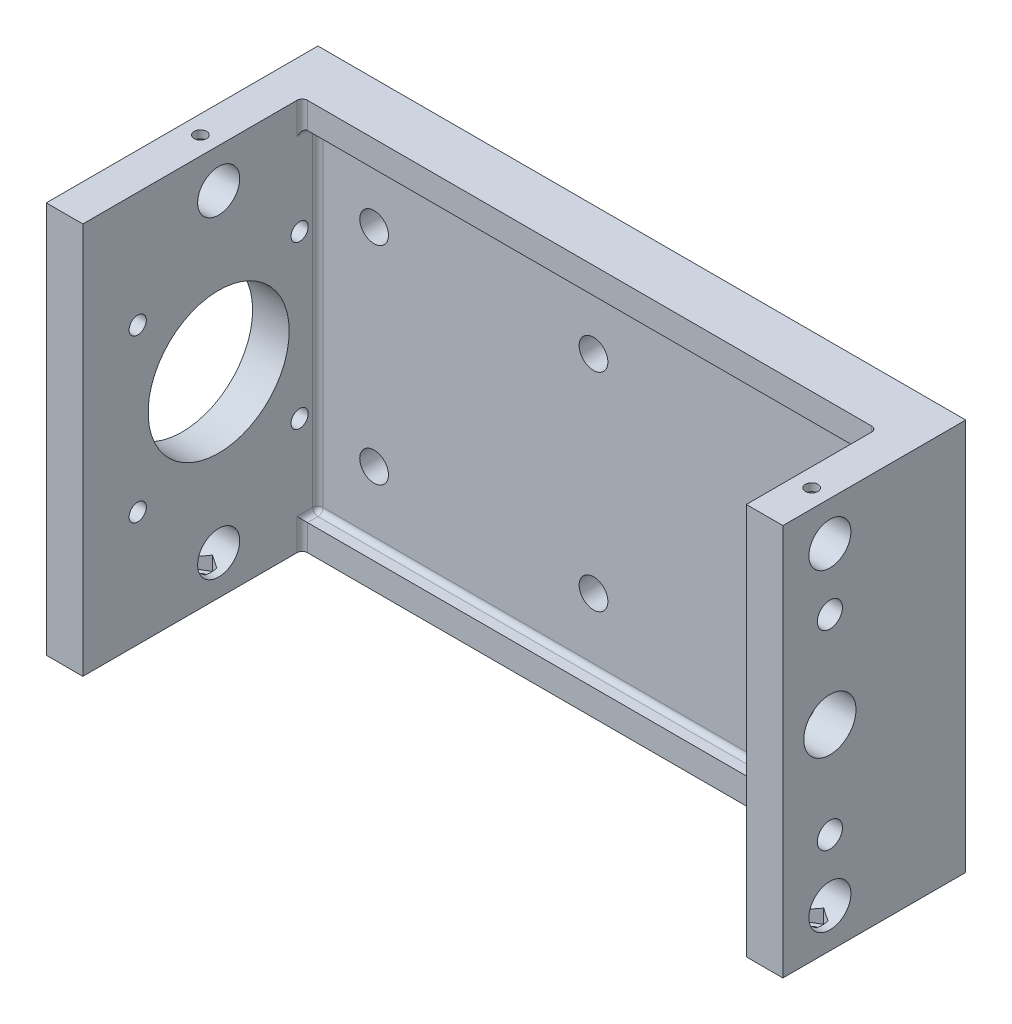
SolidWorks part; units mm, degrees
ref_plane "Plan de face" through (0, 0, 0) normal (0, 0, 1) x (1, 0, 0)
ref_plane "Plan de dessus" through (0, 0, 0) normal (0, 1, 0) x (1, 0, 0)
ref_plane "Plan de droite" through (0, 0, 0) normal (1, 0, 0) x (0, 0, -1)
sketch "Sketch1" plane through (0, 0, 0) normal (0, 0, 1) x (1, 0, 0)
  line L1 (55, -37.5) -> (-55, -37.5)
  line L2 (55, -37.5) -> (55, 37.5)
  line L3 (55, 37.5) -> (-55, 37.5)
  line L4 (-55, -37.5) -> (-55, 37.5)
  line L5 (55, -37.5) -> (-55, 37.5) construction
  line L6 (55, 37.5) -> (-55, -37.5) construction
  point P0 (0, 0)
  dimension "D1" = 110
  dimension "D2" = 75
extrude "Boss-Extrude1" add sketch "Sketch1" along normal blind 5
sketch "Sketch2" plane through (-55, 0, 0) normal (-1, 0, 0) x (0, 0, 1)
  line L0 (5, -37.5) -> (0, -37.5) construction
  line L1 (0, 37.5) -> (50, 37.5)
  line L2 (0, 37.5) -> (0, -37.5)
  line L3 (0, -37.5) -> (50, -37.5)
  line L4 (50, 37.5) -> (50, -37.5)
  line L6 (45, -16.5858) -> (45, 16.5858) construction
  dimension "D1" = 5
extrude "Boss-Extrude2" add sketch "Sketch2" along normal blind 7
sketch "Sketch3" plane through (55, 0, 0) normal (1, 0, 0) x (0, 0, -1)
  line L10 (0, 37.5) -> (-50, 37.5)
  line L11 (0, 37.5) -> (0, -37.5)
  line L12 (0, -37.5) -> (-50, -37.5)
  line L13 (-50, 37.5) -> (-50, -37.5)
extrude "Boss-Extrude3" add sketch "Sketch3" along normal blind 7
sketch "Sketch4" plane through (-55, 0, 0) normal (1, 0, 0) x (0, 0, -1)
  circle A0 centre (-24, 0) radius 13.5
  dimension "D1" = 27
extrude "Cut-Extrude1" cut sketch "Sketch4" against normal through all
sketch "Sketch5" plane through (-62, 0, 0) normal (-1, 0, 0) x (0, 0, 1)
  circle A0 centre (39.5, 15.5) radius 1.65
  circle A1 centre (39.5, -15.5) radius 1.65
  circle A2 centre (8.5, -15.5) radius 1.65
  circle A3 centre (8.5, 15.5) radius 1.65
  dimension "D1" = 3.3
  dimension "D2" = 3.3
  dimension "D3" = 3.3
  dimension "D4" = 3.3
extrude "Cut-Extrude2" cut sketch "Sketch5" against normal up to surface (7 mm away) up to face at (-55, 0, 10.5)
sketch "Sketch8" plane through (-62, 0, 0) normal (-1, 0, 0) x (0, 0, 1)
  circle A0 centre (24, 30) radius 4.025
  dimension "D1" = 8.05
extrude "Cut-Extrude5" cut sketch "Sketch8" against normal through all
mirror "Mirror1" about plane through (0, 0, 0) normal (0, 1, 0) of "Cut-Extrude5"
sketch "Sketch9" plane through (55, 0, 0) normal (-1, 0, 0) x (0, 0, 1)
  line L0 (50, -37.5) -> (5, -37.5) construction
  line L1 (50, 37.5) -> (33, 37.5)
  line L2 (50, 37.5) -> (50, -37.5)
  line L3 (50, -37.5) -> (33, -37.5)
  line L4 (33, 37.5) -> (33, -37.5)
  dimension "D1" = 17
extrude "Cut-Extrude6" cut sketch "Sketch9" against normal through all
sketch "Sketch13" plane through (0, 0, 0) normal (0, 0, -1) x (-1, 0, 0)
  line L1 (62, 37.5) -> (62, -37.5) construction
  circle A0 centre (44.25, 19.85) radius 2.75
  circle A1 centre (2.25, 19.85) radius 2.75
  circle A2 centre (2.25, -19.85) radius 2.75
  circle A3 centre (44.25, -19.85) radius 2.75
  dimension "D1" = 5.5
  dimension "D2" = 5.5
  dimension "D3" = 5.5
  dimension "D4" = 5.5
  dimension "D5" = 17.75
  dimension "D6" = 42
extrude "Cut-Extrude7" cut sketch "Sketch13" against normal blind 10
sketch "Sketch14" plane through (55, 0, 0) normal (-1, 0, 0) x (0, 0, 1)
  circle A0 centre (24, 0) radius 5
  dimension "D1" = 10
extrude "Cut-Extrude8" cut sketch "Sketch14" against normal blind 10
sketch "Sketch15" plane through (0, 0, 0) normal (0, 0, -1) x (-1, 0, 0)
  line L4 (-62, -37.5) -> (62, -37.5)
  line L5 (62, -37.5) -> (62, 37.5)
  line L6 (62, 37.5) -> (-62, 37.5)
  line L7 (-62, 37.5) -> (-62, -37.5)
  line L8 (-62, -37.5) -> (62, -37.5)
  line L9 (62, -37.5) -> (62, 37.5)
  line L10 (62, 37.5) -> (-62, 37.5)
  line L11 (-62, 37.5) -> (-62, -37.5)
  circle A1 centre (44.25, 19.85) radius 2.75
  circle A2 centre (44.25, 19.85) radius 2.75
  circle A4 centre (2.25, 19.85) radius 2.75
  circle A5 centre (2.25, -19.85) radius 2.75
  circle A6 centre (2.25, -19.85) radius 2.75
  circle A7 centre (44.25, -19.85) radius 2.75
  circle A8 centre (44.25, -19.85) radius 2.75
  point P6 (0, 19.85)
  dimension "D1" = 0
  dimension "D3" = 0
  dimension "D4" = 0
  dimension "D5" = 0
extrude "Boss-Extrude4" add sketch "Sketch15" along normal blind 2
ref_plane "Plane1" through (0, -34.025, 0) normal (0, 1, 0) x (1, 0, 0)
sketch "Sketch16" plane through (0, -34.025, 0) normal (0, 1, 0) x (1, 0, 0)
  line L0 (62, -33) -> (55, -33) construction
  line L1 (58.5, -26.3094) -> (60.5, -25.1547)
  line L2 (60.5, -25.1547) -> (60.5, -22.8453)
  line L3 (60.5, -22.8453) -> (58.5, -21.6906)
  line L4 (58.5, -21.6906) -> (56.5, -22.8453)
  line L5 (56.5, -22.8453) -> (56.5, -25.1547)
  line L6 (56.5, -25.1547) -> (58.5, -26.3094)
  line L7 (55, -5) -> (55, -33) construction
  circle A0 centre (58.5, -24) radius 2 construction
  dimension "D2" = 4
  dimension "D1" = 9
  dimension "D3" = 3.5
extrude "Cut-Extrude11" cut sketch "Sketch16" against normal blind 2 and the other way blind 2
hole_wizard "Dégagement M21" positions "Sketch17" profile "Sketch18" hole size "M2" standard "ISO"
sketch "Sketch17" plane through (0, -37.5, 0) normal (0, -1, 0) x (-1, 0, 0)
  line L0 (-62, -33) -> (-55, -33) construction
  line L1 (-62, -33) -> (-62, 2) construction
  point P9 (-58.5, -24)
  dimension "D1" = 9
  dimension "D2" = 3.5
sketch "Sketch18" plane through (58.5, -37.5, 24) normal (1, 0, 0) x (0, 0, -1)
  line L0 (0, 0) -> (0, 5.721)
  line L1 (0, 5.721) -> (1.2, 5)
  line L2 (1.2, 5) -> (1.2, 0)
  line L5 (1.2, 0) -> (0, 0)
  line L10 (0, 5.721) -> (-1.2, 5) construction
  line L11 (0, -6.35) -> (0, 107.95) construction
  dimension "Diamètre du perçage" = 2.4
  dimension "Profondeur du perçage" = 5
  dimension "Angle de pointe" = 118
mirror "Mirror5" about plane through (0, 0, 0) normal (1, 0, 0) of "Dégagement M21", "Cut-Extrude11"
mirror "Mirror7" about plane through (0, 0, 0) normal (0, 1, 0) of "Cut-Extrude11", "Dégagement M21", "Mirror5"
sketch "Sketch20" plane through (55, 0, 0) normal (-1, 0, 0) x (0, 0, 1)
  circle A0 centre (24, 18.25) radius 2.4
  circle A1 centre (24, -18.25) radius 2.4
extrude "Cut-Extrude12" cut sketch "Sketch20" against normal through all
sketch "Sketch21" plane through (0, 0, 5) normal (0, 0, 1) x (1, 0, 0)
  line L0 (-55, 37.5) -> (-55, -37.5) construction
  line L1 (55, 37.5) -> (-55, 37.5)
  line L2 (55, 37.5) -> (55, 32.5)
  line L3 (55, 32.5) -> (-55, 32.5)
  line L4 (-55, 37.5) -> (-55, 32.5)
  line L5 (55, -37.5) -> (55, 37.5) construction
  line L6 (-55, -37.5) -> (55, -37.5)
  line L7 (-55, -37.5) -> (-55, -32.5)
  line L8 (-55, -32.5) -> (55, -32.5)
  line L9 (55, -37.5) -> (55, -32.5)
  dimension "D1" = 5
  dimension "D2" = 5
extrude "Boss-Extrude5" add sketch "Sketch21" along normal blind 3
fillet "Fillet2" radius 1 12 edges at (-55, 32.5, 6.5) (-55, 35, 8) (-55, -32.5, 6.5) (-55, -35, 8) (55, 32.5, 6.5) (55, 35, 8) (55, -35, 8) (55, -32.5, 6.5) (55, 0, 5) (0, 32.5, 5) (0, -32.5, 5) (-55, 0, 5)
